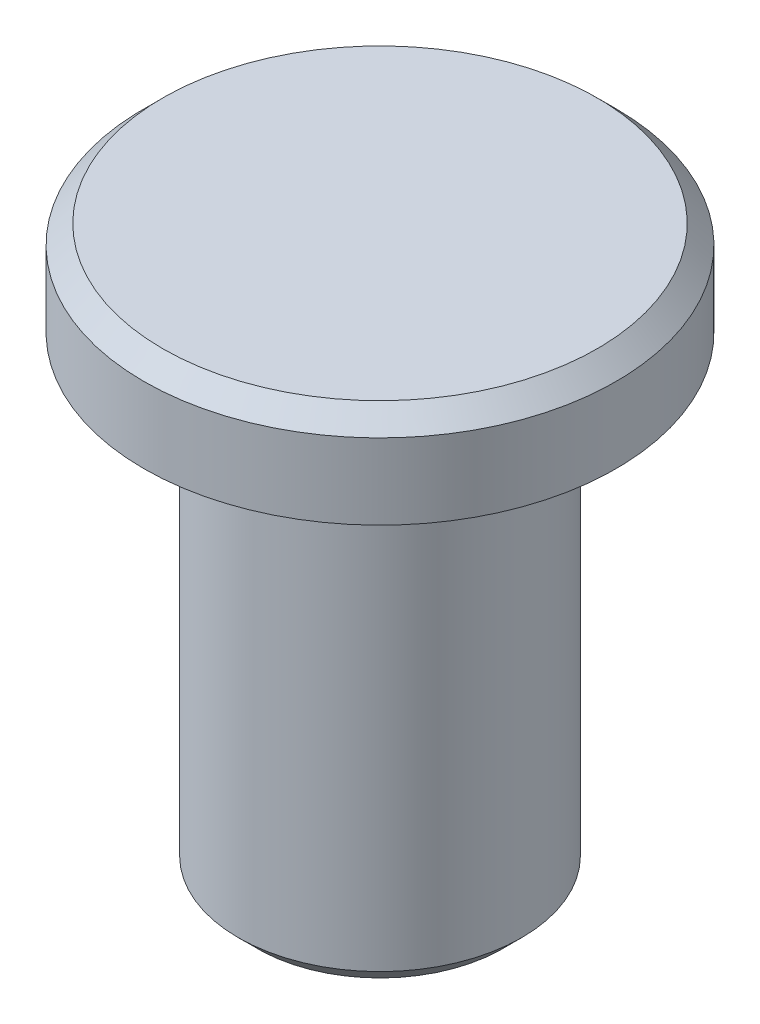
SolidWorks part; units mm, degrees
ref_plane "Front Plane" through (0, 0, 0) normal (0, 0, 1) x (1, 0, 0)
ref_plane "Top Plane" through (0, 0, 0) normal (0, 1, 0) x (1, 0, 0)
ref_plane "Right Plane" through (0, 0, 0) normal (1, 0, 0) x (0, 0, -1)
sketch "Sketch2" plane through (0, 0, 0) normal (0, 0, 1) x (1, 0, 0)
  line L0 (0, 0) -> (0, 6)
  line L1 (0, 6) -> (2.5, 6)
  line L2 (2.5, 6) -> (2.5, 5)
  line L3 (2.5, 5) -> (1.5, 5)
  line L4 (1.5, 5) -> (1.5, 0)
  line L5 (1.5, 0) -> (0, 0)
  dimension "D1" = 6
  dimension "D2" = 2.5
  dimension "D3" = 1.5
  dimension "D4" = 5
revolve "Revolve1" add sketch "Sketch2" angle 360 about L0
chamfer "Chamfer2" distance 0.2 angle 45 2 edges at (0, 0, -1.5) (0, 6, -2.5)
